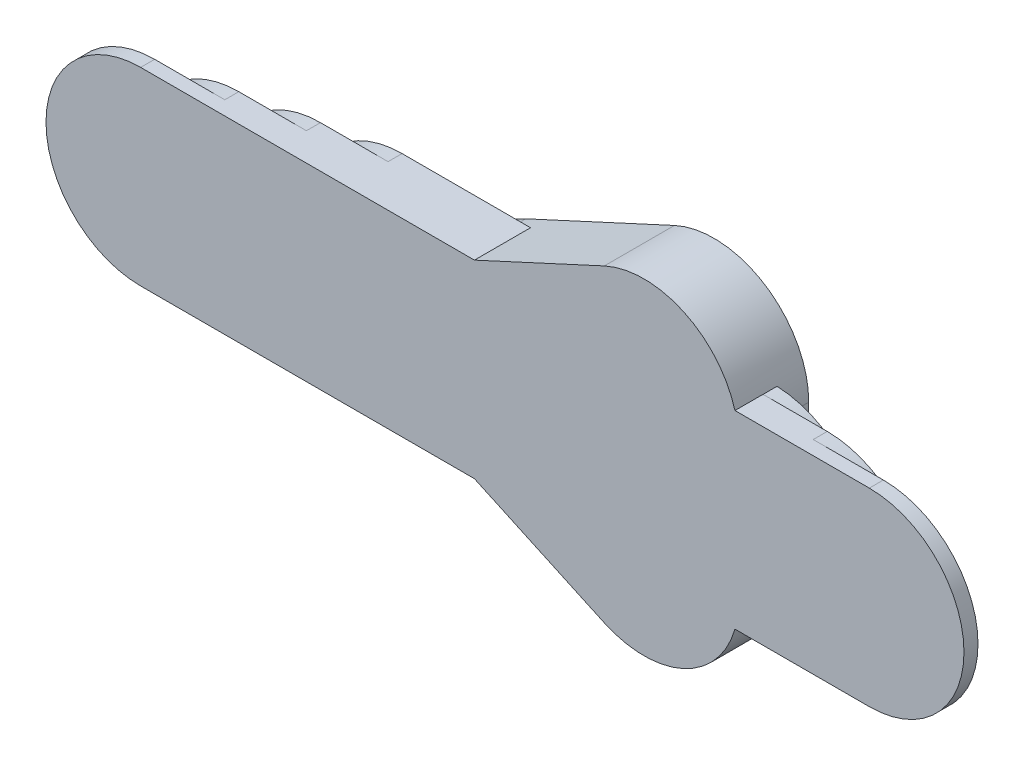
SolidWorks part; units mm, degrees
ref_plane "Front Plane" through (0, 0, 0) normal (0, 0, 1) x (1, 0, 0)
ref_plane "Top Plane" through (0, 0, 0) normal (0, 1, 0) x (1, 0, 0)
ref_plane "Right Plane" through (0, 0, 0) normal (1, 0, 0) x (0, 0, -1)
sketch "Sketch1" plane through (0, 0, 0) normal (0, 0, 1) x (1, 0, 0)
  line L1 (-31.75, 18.9) -> (31.75, 18.9)
  line L2 (-31.75, 18.9) -> (-31.75, -18.9) construction
  line L3 (-31.75, -18.9) -> (31.75, -18.9)
  line L4 (31.75, 18.9) -> (31.75, -18.9) construction
  line L5 (-31.75, 18.9) -> (31.75, -18.9) construction
  line L6 (-31.75, -18.9) -> (31.75, 18.9) construction
  arc A0 (-31.75, 18.9) -> (-31.75, -18.9) centre (-31.75, 0) ccw
  arc A1 (31.75, 18.9) -> (31.75, -18.9) centre (31.75, 0) cw
  point P0 (0, 0)
  point P8 (-50.65, 0)
  point P9 (50.65, 0)
  dimension "D1" = 37.8
  dimension "D2" = 101.3
extrude "Boss-Extrude1" add sketch "Sketch1" along normal blind 2.8
sketch "Sketch5" plane through (0, 0, 0) normal (0, 0, -1) x (-1, 0, 0)
  line L4 (-25.9419, 32.6) -> (-126.1347, 32.6) construction
  line L5 (47.072, 0) -> (-46.65, 0) construction
  line L6 (-46.65, 0) -> (-46.65, 43.232) construction
  line L7 (-46.65, 43.232) -> (47.072, 0) construction
  line L8 (20.85, -23.5132) -> (20.85, 2.4291) construction
  line L9 (-46.65, -13.7) -> (-46.65, 13.7)
  line L10 (-19.8335, 30.8621) -> (9.8665, 17.1621)
  line L11 (-19.8335, -30.8621) -> (9.8665, -17.1621)
  arc A3 (9.8665, -17.1621) -> (9.8665, 17.1621) centre (1.95, 0) ccw
  arc A4 (-46.65, 13.7) -> (-19.8335, 30.8621) centre (-27.75, 13.7) cw
  arc A5 (-46.65, -13.7) -> (-19.8335, -30.8621) centre (-27.75, -13.7) ccw
  arc A7 (-31.75, 18.9) -> (-31.75, -18.9) centre (-31.75, 0) ccw construction
  point P3 (0, 0)
  point P11 (20.85, 0)
  point P13 (0, 0)
  point P15 (-17.9759, -2.5056)
  point P16 (-27.3876, 0)
  point P22 (-10.8674, 0)
  point P23 (47.0112, 0)
  point P30 (-50.65, 0)
  dimension "D1" = 18.9
  dimension "D3" = 67.5
  dimension "D2" = 32.6
  dimension "D4" = 4
extrude "Boss-Extrude5" add sketch "Sketch5" along normal blind 2.8
sketch "Sketch2" plane through (0, 0, 2.8) normal (0, 0, 1) x (1, 0, 0)
  line L0 (31.75, 18.9) -> (-31.75, 18.9) construction
  line L1 (-45.25, 18.9) -> (45.25, 18.9)
  line L2 (-45.25, 18.9) -> (-45.25, -18.9) construction
  line L3 (-45.25, -18.9) -> (45.25, -18.9)
  line L4 (45.25, 18.9) -> (45.25, -18.9) construction
  line L5 (-45.25, 18.9) -> (45.25, -18.9) construction
  line L6 (-45.25, -18.9) -> (45.25, 18.9) construction
  arc A0 (-45.25, 18.9) -> (-45.25, -18.9) centre (-45.25, 0) ccw
  arc A1 (45.25, 18.9) -> (45.25, -18.9) centre (45.25, 0) cw
  point P0 (0, 0)
  point P10 (97.868, 0)
  point P11 (-64.15, 0)
  point P12 (64.15, 0)
  point P13 (0, 0)
  dimension "D1" = 128.3
extrude "Boss-Extrude2" add sketch "Sketch2" along normal blind 2.8
sketch "Sketch3" plane through (0, 0, 5.6) normal (0, 0, 1) x (1, 0, 0)
  line L0 (45.25, 18.9) -> (-45.25, 18.9) construction
  line L1 (-58.75, 18.9) -> (58.75, 18.9)
  line L2 (-58.75, 18.9) -> (-58.75, -18.9) construction
  line L3 (-58.75, -18.9) -> (58.75, -18.9)
  line L4 (58.75, 18.9) -> (58.75, -18.9) construction
  line L5 (-58.75, 18.9) -> (58.75, -18.9) construction
  line L6 (-58.75, -18.9) -> (58.75, 18.9) construction
  arc A0 (-58.75, 18.9) -> (-58.75, -18.9) centre (-58.75, 0) ccw
  arc A1 (58.75, 18.9) -> (58.75, -18.9) centre (58.75, 0) cw
  point P0 (0, 0)
  point P10 (-77.65, 0)
  point P11 (77.65, 0)
  point P12 (0, 0)
  point P13 (0, 0)
  dimension "D1" = 155.3
extrude "Boss-Extrude3" add sketch "Sketch3" along normal blind 2.8
sketch "Sketch4" plane through (0, 0, 8.4) normal (0, 0, 1) x (1, 0, 0)
  line L0 (58.75, 18.9) -> (-58.75, 18.9) construction
  line L1 (-72.75, 18.9) -> (72.75, 18.9)
  line L2 (-72.75, 18.9) -> (-72.75, -18.9) construction
  line L3 (-72.75, -18.9) -> (72.75, -18.9)
  line L4 (72.75, 18.9) -> (72.75, -18.9) construction
  line L5 (-72.75, 18.9) -> (72.75, -18.9) construction
  line L6 (-72.75, -18.9) -> (72.75, 18.9) construction
  arc A0 (-72.75, 18.9) -> (-72.75, -18.9) centre (-72.75, 0) ccw
  arc A1 (72.75, 18.9) -> (72.75, -18.9) centre (72.75, 0) cw
  point P0 (0, 0)
  point P10 (-91.65, 0)
  point P11 (91.65, 0)
  dimension "D1" = 183.3
extrude "Boss-Extrude4" add sketch "Sketch4" along normal blind 2.8
sketch "Sketch7" plane through (0, 0, 0) normal (0, 0, 1) x (1, 0, 0)
  line L3 (31.75, -18.9) -> (-6.099, -18.9)
  line L4 (-6.099, -18.9) -> (19.8335, -30.8621)
  line L5 (46.65, -13.7) -> (46.65, -11.6276)
  line L6 (31.75, -18.9) -> (-6.099, -18.9)
  line L7 (-6.099, -18.9) -> (19.8335, -30.8621)
  line L8 (46.65, -13.7) -> (46.65, -11.6276)
  line L9 (46.65, 11.6276) -> (46.65, 13.7)
  line L10 (19.8335, 30.8621) -> (-6.099, 18.9)
  line L11 (-6.099, 18.9) -> (31.75, 18.9)
  line L12 (46.65, 11.6276) -> (46.65, 13.7)
  line L13 (19.8335, 30.8621) -> (-6.099, 18.9)
  line L14 (-6.099, 18.9) -> (31.75, 18.9)
  arc A2 (31.75, -18.9) -> (46.65, -11.6276) centre (31.75, 0) ccw
  arc A3 (19.8335, -30.8621) -> (46.65, -13.7) centre (27.75, -13.7) ccw
  arc A4 (31.75, -18.9) -> (46.65, -11.6276) centre (31.75, 0) ccw
  arc A5 (19.8335, -30.8621) -> (46.65, -13.7) centre (27.75, -13.7) ccw
  arc A6 (46.65, 11.6276) -> (31.75, 18.9) centre (31.75, 0) ccw
  arc A7 (46.65, 13.7) -> (19.8335, 30.8621) centre (27.75, 13.7) ccw
  arc A8 (46.65, 11.6276) -> (31.75, 18.9) centre (31.75, 0) ccw
  arc A9 (46.65, 13.7) -> (19.8335, 30.8621) centre (27.75, 13.7) ccw
  dimension "D1" = 0
  dimension "D2" = 0
extrude "Boss-Extrude6" add sketch "Sketch7" along normal up to surface (11.2 mm away) up to face at (0, 0, 11.2)
sketch "Sketch10" plane through (0, 0, -2.8) normal (0, 0, -1) x (-1, 0, 0)
  arc A0 (18.0098, -9.9646) -> (18.0098, 9.9646) centre (18.85, 0) ccw
  arc A1 (9.8665, -17.1621) -> (9.8665, 17.1621) centre (1.95, 0) ccw construction
  arc A2 (18.0098, -9.9646) -> (18.0098, 9.9646) centre (1.95, 0) ccw
  point P3 (28.85, 0)
  point P8 (0, 0)
  point P9 (11.2636, 0)
  point P10 (20.85, 0)
  dimension "D1" = 8
  dimension "D2" = 10
extrude "Boss-Extrude7" add sketch "Sketch10" against normal up to surface (2.8 mm away) up to face at (-20.8858, 0, 0)
